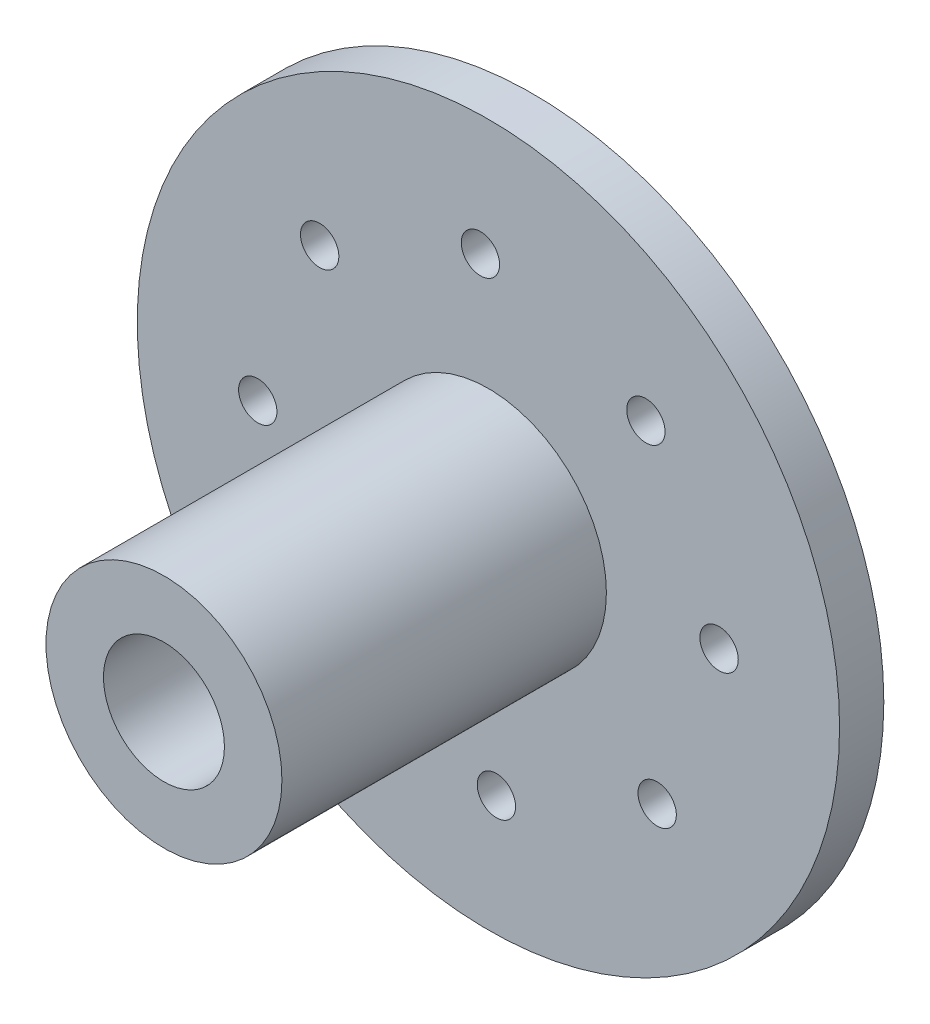
SolidWorks part; units mm, degrees
ref_plane "Plan de face" through (0, 0, 0) normal (0, 0, 1) x (1, 0, 0)
ref_plane "Plan de dessus" through (0, 0, 0) normal (0, 1, 0) x (1, 0, 0)
ref_plane "Plan de droite" through (0, 0, 0) normal (1, 0, 0) x (0, 0, -1)
sketch "Esquisse1" plane through (0, 0, 0) normal (0, 0, 1) x (1, 0, 0)
  circle A0 centre (0, 0) radius 23.81
  dimension "D1" = 47.62
extrude "Boss.-Extru.1" add sketch "Esquisse1" along normal blind 3
sketch "Esquisse2" plane through (0, 0, 3) normal (0, 0, 1) x (1, 0, 0)
  circle A0 centre (0, 0) radius 8
  dimension "D1" = 16
extrude "Boss.-Extru.2" add sketch "Esquisse2" along normal blind 22
sketch "Esquisse3" plane through (0, 0, 3) normal (0, 0, 1) x (1, 0, 0)
  circle A1 centre (-11.4421, 10.6771) radius 1.3
  circle A2 centre (-0.541, 15.6406) radius 1.3
  circle A3 centre (10.6771, 11.4421) radius 1.3
  circle A4 centre (15.6406, 0.541) radius 1.3
  circle A5 centre (11.4421, -10.6771) radius 1.3
  circle A6 centre (0.541, -15.6406) radius 1.3
  circle A7 centre (-10.6771, -11.4421) radius 1.3
  circle A8 centre (-15.6406, -0.541) radius 1.3
  point P21 (0, 0)
  dimension "D2" = 2.6
  dimension "D3" = 8
extrude "Enlèv. mat.-Extru.1" cut sketch "Esquisse3" against normal blind 24
sketch "Esquisse4" plane through (0, 0, 25) normal (0, 0, 1) x (1, 0, 0)
  circle A0 centre (0, 0) radius 4.1
  dimension "D1" = 8.2
extrude "Enlèv. mat.-Extru.2" cut sketch "Esquisse4" against normal blind 18.5
sketch "Esquisse5" plane through (0, 0, 0) normal (0, 0, -1) x (-1, 0, 0)
  circle A0 centre (0, 0) radius 0.4
  dimension "D1" = 0.8
extrude "Enlèv. mat.-Extru.3" cut sketch "Esquisse5" against normal blind 10
sketch "Esquisse6" plane through (0, 0, 0) normal (0, 0, -1) x (-1, 0, 0)
  circle A0 centre (0, 0) radius 4.1
extrude "Enlèv. mat.-Extru.4" cut sketch "Esquisse6" against normal blind 1
